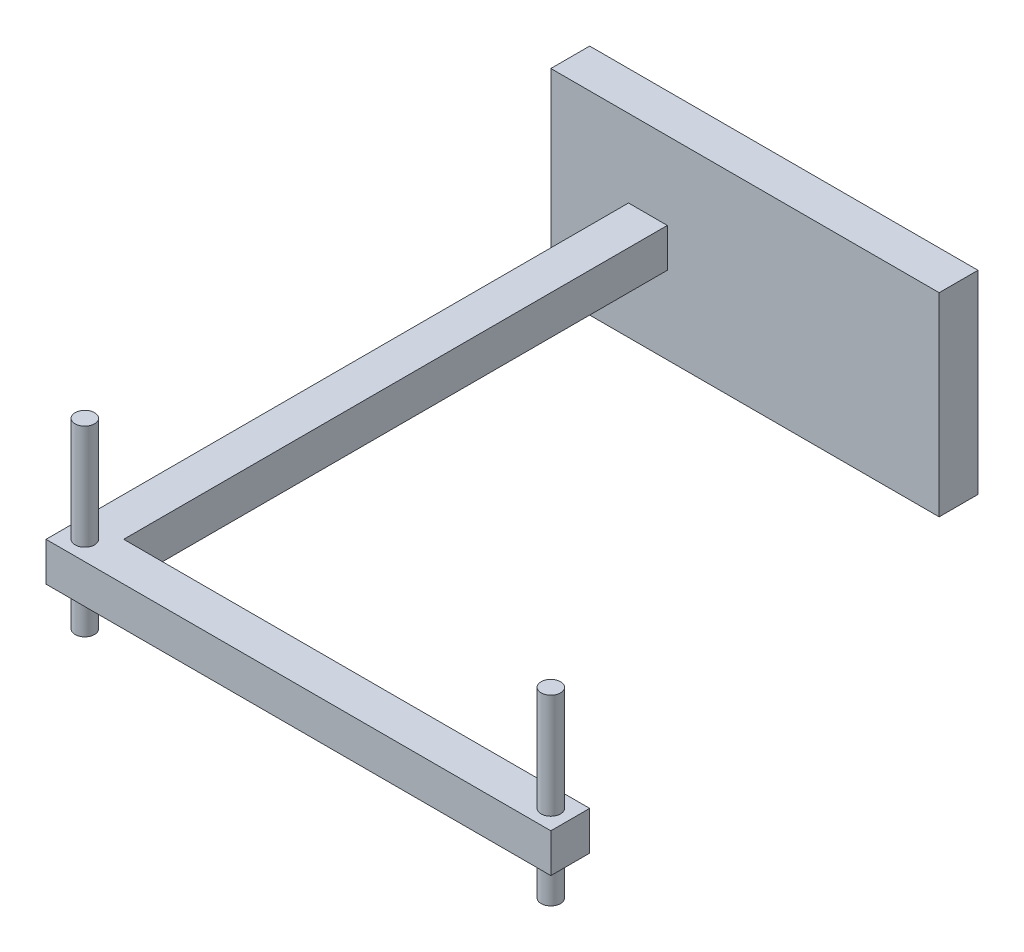
SolidWorks part; units mm, degrees
ref_plane "Front Plane" through (0, 0, 0) normal (0, 0, 1) x (1, 0, 0)
ref_plane "Top Plane" through (0, 0, 0) normal (0, 1, 0) x (1, 0, 0)
ref_plane "Right Plane" through (0, 0, 0) normal (1, 0, 0) x (0, 0, -1)
sketch "Sketch1" plane through (0, 0, 0) normal (0, 0, 1) x (1, 0, 0)
  line L1 (-50, 25) -> (50, 25)
  line L2 (-50, 25) -> (-50, -25)
  line L3 (-50, -25) -> (50, -25)
  line L4 (50, 25) -> (50, -25)
  line L5 (-50, 25) -> (50, -25) construction
  line L6 (-50, -25) -> (50, 25) construction
  point P0 (0, 0)
  dimension "D1" = 50
  dimension "D2" = 100
extrude "Boss-Extrude1" add sketch "Sketch1" along normal blind 10
sketch "Sketch2" plane through (0, 0, 10) normal (0, 0, 1) x (1, 0, 0)
  line L1 (-20, 5) -> (-30, 5)
  line L2 (-20, 5) -> (-20, -5)
  line L3 (-20, -5) -> (-30, -5)
  line L4 (-30, 5) -> (-30, -5)
  line L5 (-20, 5) -> (-30, -5) construction
  line L6 (-20, -5) -> (-30, 5) construction
  point P0 (-25, 0)
  dimension "D1" = 0
  dimension "D2" = 10
  dimension "D3" = 10
  dimension "D4" = 25
extrude "Boss-Extrude2" add sketch "Sketch2" along normal blind 150
sketch "Sketch3" plane through (-20, 0, 0) normal (1, 0, 0) x (0, 0, -1)
  line L0 (-160, -5) -> (-160, 5) construction
  line L1 (-150, 5) -> (-160, 5)
  line L2 (-150, 5) -> (-150, -5)
  line L3 (-150, -5) -> (-160, -5)
  line L4 (-160, 5) -> (-160, -5)
  line L5 (-150, 5) -> (-160, -5) construction
  line L6 (-150, -5) -> (-160, 5) construction
  line L7 (-160, 5) -> (-10, 5) construction
  point P0 (-155, 0)
  dimension "D1" = 0
  dimension "D2" = 0
  dimension "D3" = 10
  dimension "D4" = 10
extrude "Boss-Extrude3" add sketch "Sketch3" along normal blind 120
sketch "Sketch4" plane through (0, -5, 0) normal (0, -1, 0) x (1, 0, 0)
  line L0 (-30, 160) -> (100, 160) construction
  line L1 (-30, 160) -> (-30, 10) construction
  line L2 (100, 160) -> (100, 150) construction
  line L3 (100, 150) -> (-20, 150) construction
  circle A0 centre (-25, 155) radius 2.5
  circle A1 centre (95, 155) radius 2.5
  dimension "D1" = 5
  dimension "D3" = 5
  dimension "D5" = 5
  dimension "D6" = 5
  dimension "D2" = 5
  dimension "D4" = 5
extrude "Boss-Extrude4" add sketch "Sketch4" along normal blind 10
sketch "Sketch5" plane through (0, 5, -5) normal (0, -1, 0) x (-1, 0, 0)
  circle A0 centre (-95, -160) radius 2.5
  circle A1 centre (25, -160) radius 2.5
  dimension "D3" = 5
  dimension "D6" = 5
extrude "Boss-Extrude5" add sketch "Sketch5" against normal blind 27
